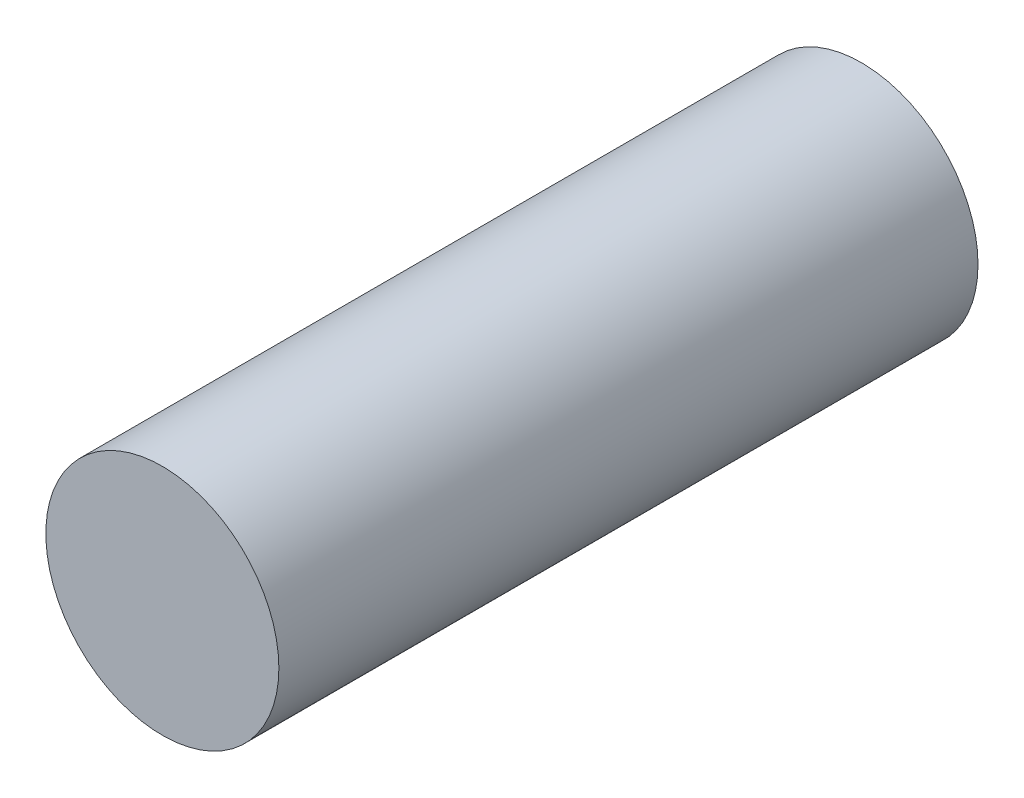
SolidWorks part; units mm, degrees
ref_plane "Front Plane" through (0, 0, 0) normal (0, 0, 1) x (1, 0, 0)
ref_plane "Top Plane" through (0, 0, 0) normal (0, 1, 0) x (1, 0, 0)
ref_plane "Right Plane" through (0, 0, 0) normal (1, 0, 0) x (0, 0, -1)
sketch "Sketch1" plane through (0, 0, 0) normal (0, 0, 1) x (1, 0, 0)
  circle A0 centre (0, 0) radius 12.5
extrude "Boss-Extrude1" add sketch "Sketch1" along normal mid plane 75
